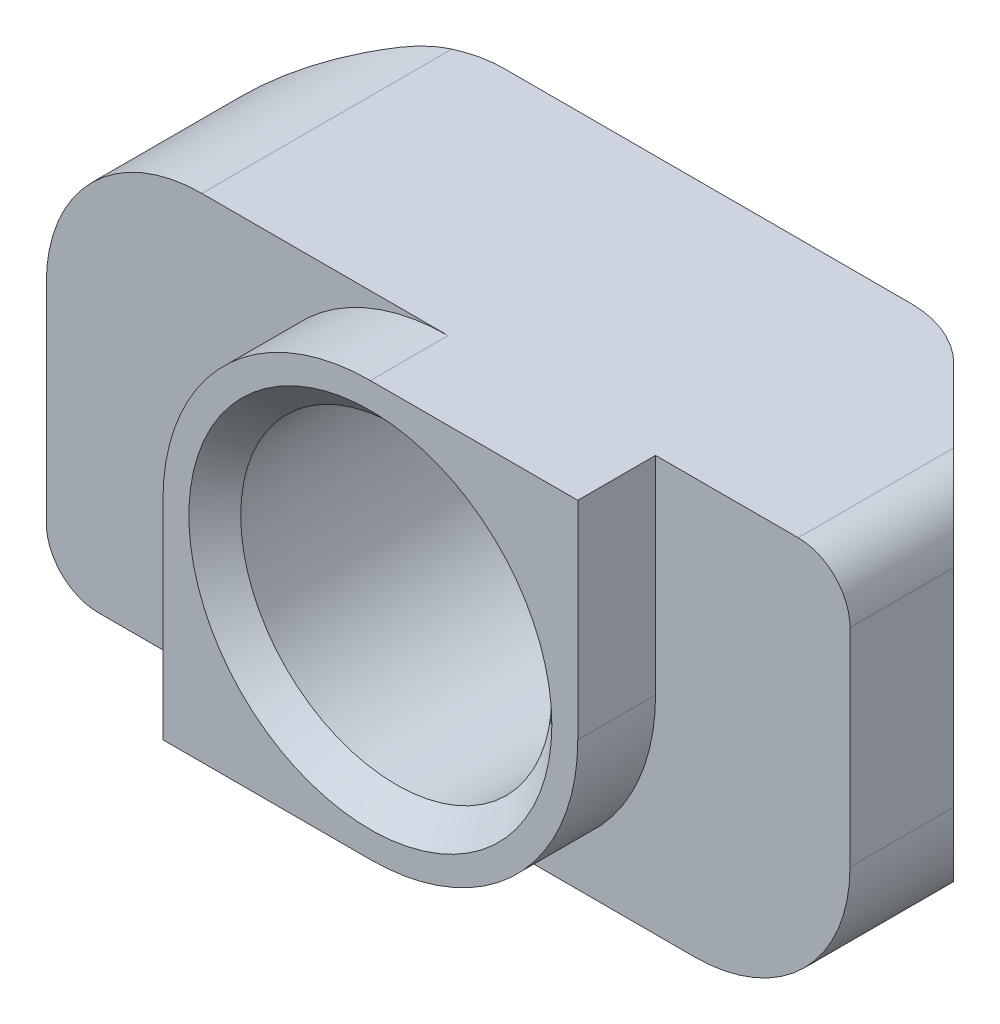
SolidWorks part; units mm, degrees
ref_plane "前视基准面" through (0, 0, 0) normal (0, 0, 1) x (1, 0, 0)
ref_plane "上视基准面" through (0, 0, 0) normal (0, 1, 0) x (1, 0, 0)
ref_plane "右视基准面" through (0, 0, 0) normal (1, 0, 0) x (0, 0, -1)
other "Configuration Table"
ref_plane "基准面1" through (0, 4, 0) normal (0, 1, 0) x (1, 0, 0)
sketch "草图1" plane through (0, 4, 0) normal (0, 1, 0) x (1, 0, 0)
  line L0 (-7.75, -3) -> (-7.75, -6.5)
  line L1 (-7.75, -6.5) -> (7.75, -6.5)
  line L2 (7.75, -6.5) -> (7.75, -3)
  line L3 (7.75, -3) -> (4.75, 0)
  line L4 (4.75, 0) -> (-4.75, 0)
  line L5 (-4.75, 0) -> (-7.75, -3)
extrude "凸台-拉伸1" add sketch "草图1" against normal blind 8
sketch "草图2" plane through (0, -4, 0) normal (0, -1, 0) x (1, 0, 0)
  line L0 (-4, 5) -> (-4, 6.5)
  line L1 (-4, 6.5) -> (-7.75, 6.5)
  line L2 (-7.75, 6.5) -> (-7.75, 5)
  line L3 (-7.75, 5) -> (-4, 5)
extrude "切除-拉伸1" cut sketch "草图2" against normal through all
sketch "草图3" plane through (0, -4, 0) normal (0, -1, 0) x (1, 0, 0)
  line L0 (4, 6.5) -> (4, 5)
  line L1 (4, 5) -> (7.75, 5)
  line L2 (7.75, 5) -> (7.75, 6.5)
  line L3 (7.75, 6.5) -> (4, 6.5)
extrude "切除-拉伸2" cut sketch "草图3" against normal through all
hole_wizard "Ø6.0 (6) 直径孔1" positions "草图5" profile "草图4" hole size "Ø6.0" standard "ANSI Metric"
sketch "草图5" plane through (0, 0, 0) normal (0, 0, -1) x (-1, 0, 0)
  point P0 (0, 0)
sketch "草图4" plane through (0, 0, 0) normal (1, 0, 0) x (0, 1, 0)
  line L0 (0, 0) -> (0, 6.5)
  line L1 (0, 6.5) -> (3, 6.5)
  line L2 (3, 6.5) -> (3, 0)
  line L5 (3, 0) -> (0, 0)
  line L11 (0, -6.35) -> (0, 107.95) construction
  dimension "通孔孔直径" = 6
  dimension "通孔孔深度" = 6.5
chamfer "倒角1" distance 0.5 angle 45 2 edges at (-3, 0, 6.5) (-3, 0, 0)
fillet "圆角1" radius 1 2 edges at (-7.75, -4, 4) (7.75, 4, 4)
fillet "圆角2" radius 2 2 edges at (4.75, 0, 0) (-4.75, 0, 0)
fillet "圆角3" radius 3 2 edges at (7.75, -4, 4) (-7.75, 4, 4)
fillet "圆角4" radius 4 2 edges at (4, -4, 5.75) (-4, 4, 5.75)
